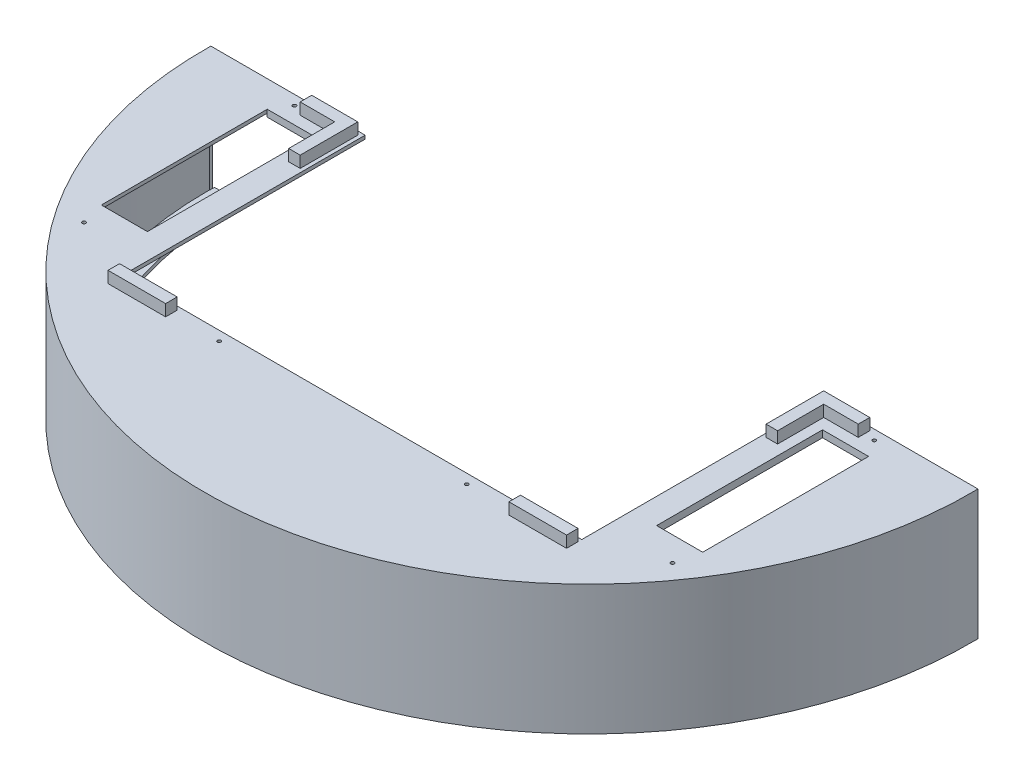
SolidWorks part; units mm, degrees
ref_plane "Front Plane" through (0, 0, 0) normal (0, 0, 1) x (1, 0, 0)
ref_plane "Top Plane" through (0, 0, 0) normal (0, 1, 0) x (1, 0, 0)
ref_plane "Right Plane" through (0, 0, 0) normal (1, 0, 0) x (0, 0, -1)
sketch "Sketch3" plane through (0, 0, 0) normal (0, 1, 0) x (1, 0, 0)
  line L0 (-251.0083, -74.5986) -> (228.9917, -74.5986) construction
  line L1 (228.9917, -74.5986) -> (-11.0083, 165.4014) construction
  line L2 (-11.0083, 165.4014) -> (-251.0083, -74.5986) construction
  line L3 (-11.0083, 165.4014) -> (-11.0083, -74.5986) construction
  line L4 (-230.0083, 0.4014) -> (-230.0083, -149.5986) construction
  line L5 (-230.0083, -149.5986) -> (-272.0083, -149.5986) construction
  line L6 (-272.0083, -149.5986) -> (-272.0083, -169.5986) construction
  line L7 (-161.0083, -209.5986) -> (138.9917, -209.5986) construction
  line L8 (-230.0083, 0.4014) -> (-272.0083, 0.4014) construction
  line L9 (-272.0083, 0.4014) -> (-272.0083, 110.4014) construction
  line L10 (-272.0083, 110.4014) -> (-121.0083, 282.0601) construction
  line L11 (-161.0083, -209.5986) -> (-272.0083, -169.5986) construction
  line L12 (249.9917, 110.4014) -> (98.9917, 282.0601) construction
  line L13 (138.9917, -209.5986) -> (249.9917, -169.5986) construction
  line L14 (249.9917, -149.5986) -> (249.9917, -169.5986) construction
  line L15 (207.9917, -149.5986) -> (249.9917, -149.5986) construction
  line L16 (207.9917, 0.4014) -> (207.9917, -149.5986) construction
  line L17 (207.9917, 0.4014) -> (249.9917, 0.4014) construction
  line L18 (249.9917, 0.4014) -> (249.9917, 110.4014) construction
  arc A0 (98.9917, 282.0601) -> (-121.0083, 282.0601) centre (-11.0083, 187.4993) ccw construction
  circle A1 centre (-11.0083, 15.1744) radius 330
  circle A2 centre (-11.0083, 15.1744) radius 333
  point P22 (-11.0083, 282.0601)
  dimension "D1" = 480
  dimension "D2" = 21
  dimension "D3" = 75
  dimension "D4" = 75
  dimension "D5" = 42
  dimension "D6" = 20
  dimension "D7" = 110
  dimension "D8" = 110
  dimension "D9" = 240
  dimension "D10" = 20
  dimension "D11" = 21
  dimension "D12" = 21
  dimension "D13" = 150
  dimension "D14" = 42
  dimension "D15" = 300
  dimension "D16" = 3
extrude "Boss-Extrude2" add sketch "Sketch3" along normal blind 3 and the other way blind 109.6
ref_plane "Plane2" through (0, -104.6, 0) normal (0, -1, 0) x (-1, 0, 0)
sketch "Sketch5" plane through (0, -104.6, 0) normal (0, -1, 0) x (1, 0, 0)
  line L0 (-166.0669, -282.0601) -> (144.0503, -282.0601) construction
  line L1 (-164.3328, -283.0601) -> (142.3162, -283.0601)
  circle A0 centre (-11.0083, -15.1744) radius 330
  circle A1 centre (-11.0083, -15.1744) radius 308.6602 construction
  arc A2 (-164.3328, -283.0601) -> (142.3162, -283.0601) centre (-11.0083, -15.1744) cw
  dimension "D1" = 1
extrude "Boss-Extrude4" add sketch "Sketch5" against normal blind 3
sketch "Sketch6" plane through (0, 0, 0) normal (0, 1, 0) x (1, 0, 0)
  line L0 (-272.0083, 0.4014) -> (-272.0083, 110.4014) construction
  line L1 (249.9917, 0.4014) -> (249.9917, 110.4014) construction
  line L2 (249.9917, 110.4014) -> (98.9917, 282.0601) construction
  line L3 (-272.0083, 110.4014) -> (-121.0083, 282.0601) construction
  line L4 (-82.3339, 288.1744) -> (60.3173, 288.1744)
  line L5 (-100.8342, 348.1744) -> (51.1218, 348.1744) construction
  line L6 (-247.0083, 20.4014) -> (-247.0083, 100.9705)
  line L7 (-230.0083, 0.4014) -> (-230.0083, -149.5986) construction
  line L8 (-247.0083, 20.4014) -> (-210.0083, 20.4014)
  line L9 (224.9917, 20.4014) -> (224.9917, 100.9705)
  line L10 (207.9917, 0.4014) -> (249.9917, 0.4014) construction
  line L11 (224.9917, 20.4014) -> (187.9917, 20.4014)
  line L12 (-247.0083, 100.9705) -> (-82.3339, 288.1744)
  line L13 (224.9917, 100.9705) -> (60.3173, 288.1744)
  line L14 (-210.0083, 20.4014) -> (-210.0083, -191.941) construction
  line L15 (187.9917, 20.4014) -> (187.9917, -191.941) construction
  line L16 (138.9917, -209.5986) -> (249.9917, -169.5986) construction
  line L17 (-161.0083, -209.5986) -> (-272.0083, -169.5986) construction
  line L18 (-210.0083, -189.5986) -> (187.9917, -189.5986)
  line L19 (-161.0083, -209.5986) -> (138.9917, -209.5986) construction
  line L20 (-210.0083, 20.4014) -> (-210.0083, -189.5986)
  line L21 (187.9917, -189.5986) -> (187.9917, 20.4014)
  line L22 (-230.0083, 0.4014) -> (-272.0083, 0.4014) construction
  circle A0 centre (-11.0083, 15.1744) radius 333
  circle A1 centre (-11.0083, 15.1744) radius 273 construction
  dimension "D1" = 60
  dimension "D2" = 25
  dimension "D3" = 25
  dimension "D4" = 25
  dimension "D5" = 25
  dimension "D6" = 60
  dimension "D7" = 20
  dimension "D8" = 20
  dimension "D9" = 20
  dimension "D10" = 20
extrude "Boss-Extrude6" add sketch "Sketch6" along normal blind 3 contours A0 L21 L18 L20 L8 L6 L12 L4 L13 L9 L11
ref_plane "Plane4" through (0, -5, 0) normal (0, 1, 0) x (1, 0, 0)
sketch "Sketch17" plane through (0, -5, 0) normal (0, 1, 0) x (1, 0, 0)
  line L2 (142.3162, 283.0601) -> (-164.3328, 283.0601)
  line L3 (142.3162, 283.0601) -> (-164.3328, 283.0601)
  arc A2 (-164.3328, 283.0601) -> (142.3162, 283.0601) centre (-11.0083, 15.1744) ccw
  arc A3 (-164.3328, 283.0601) -> (142.3162, 283.0601) centre (-11.0083, 15.1744) ccw
  circle A5 centre (-11.0083, 15.1744) radius 330
  circle A6 centre (-11.0083, 15.1744) radius 330
  dimension "D1" = 0
  dimension "D2" = 0
extrude "Boss-Extrude9" add sketch "Sketch17" against normal blind 3
sketch "Sketch18" plane through (0, -5, 0) normal (0, 1, 0) x (1, 0, 0)
  line L1 (-363.4395, 20.4014) -> (349.2765, 20.4014)
  line L2 (-363.4395, 20.4014) -> (-363.4395, 366.6238)
  line L3 (-363.4395, 366.6238) -> (349.2765, 366.6238)
  line L4 (349.2765, 20.4014) -> (349.2765, 366.6238)
extrude "Cut-Extrude1" cut sketch "Sketch18" against normal through all both and the other way through all
sketch "Sketch19" plane through (0, 3, 0) normal (0, 1, 0) x (1, 0, 0)
  line L1 (-213.2083, 17.2014) -> (-223.2083, 17.2014)
  line L2 (-213.2083, 17.2014) -> (-213.2083, -32.7986)
  line L3 (-213.2083, -32.7986) -> (-223.2083, -32.7986)
  line L4 (-223.2083, 17.2014) -> (-223.2083, -32.7986)
  line L5 (191.1917, 17.2014) -> (201.1917, 17.2014)
  line L6 (191.1917, 17.2014) -> (191.1917, -32.7986)
  line L7 (191.1917, -32.7986) -> (201.1917, -32.7986)
  line L8 (201.1917, 17.2014) -> (201.1917, -32.7986)
  line L9 (-210.0083, -192.7986) -> (-160.0083, -192.7986)
  line L10 (-210.0083, -192.7986) -> (-210.0083, -202.7986)
  line L11 (-210.0083, -202.7986) -> (-160.0083, -202.7986)
  line L12 (-210.0083, 20.4014) -> (-210.0083, -189.5986) construction
  line L13 (201.1917, 17.2014) -> (231.1917, 17.2014)
  line L14 (201.1917, 17.2014) -> (201.1917, 7.2014)
  line L15 (201.1917, 7.2014) -> (231.1917, 7.2014)
  line L16 (231.1917, 17.2014) -> (231.1917, 7.2014)
  line L17 (-223.2083, 17.2014) -> (-253.2083, 17.2014)
  line L18 (-223.2083, 17.2014) -> (-223.2083, 7.2014)
  line L19 (-223.2083, 7.2014) -> (-253.2083, 7.2014)
  line L20 (-253.2083, 17.2014) -> (-253.2083, 7.2014)
  line L21 (-343.9673, 20.4014) -> (-210.0083, 20.4014) construction
  line L22 (321.9507, 20.4014) -> (187.9917, 20.4014) construction
  line L23 (187.9917, -189.5986) -> (187.9917, 20.4014) construction
  line L24 (-210.0083, -189.5986) -> (187.9917, -189.5986) construction
  line L29 (-160.0083, -192.7986) -> (-160.0083, -202.7986)
  line L30 (187.9917, -202.7986) -> (137.9917, -202.7986)
  line L31 (187.9917, -202.7986) -> (187.9917, -192.7986)
  line L32 (187.9917, -192.7986) -> (137.9917, -192.7986)
  line L33 (137.9917, -202.7986) -> (137.9917, -192.7986)
  dimension "D5" = 50
  dimension "D6" = 10
  dimension "D7" = 30
  dimension "D8" = 10
  dimension "D9" = 30
  dimension "D10" = 10
  dimension "D3" = 3.2
  dimension "D4" = 3.2
  dimension "D2" = 3.2
  dimension "D11" = 3.2
  dimension "D15" = 50
  dimension "D16" = 10
  dimension "D17" = 50
extrude "Boss-Extrude10" add sketch "Sketch19" along normal blind 10 contours L29 L9 L10 L11 | L33 L30 L31 L32 | L8 L5 L6 L7 | L16 L13 L8 L15 | L17 L20 L19 L4 | L1 L4 L3 L2
sketch "Sketch20" plane through (0, 0, -20.4014) normal (0, 0, -1) x (-1, 0, 0)
  line L0 (-318.9503, 0) -> (-318.9917, -109.6) construction
  line L1 (-318.9917, -109.6) -> (-320.4505, -109.6) construction
  line L2 (-318.9503, -109.6) -> (-321.9507, -109.6) construction
  line L3 (-320.4505, -109.6) -> (-320.4505, 0) construction
  line L4 (-320.4505, 0) -> (-318.9503, 0) construction
  line L5 (340.9669, 0) -> (340.9669, -109.6) construction
  line L6 (340.9669, -109.6) -> (342.4671, -109.6) construction
  line L7 (343.9673, -109.6) -> (340.9669, -109.6) construction
  line L8 (342.4671, -109.6) -> (342.4671, 0) construction
  line L9 (342.4671, 0) -> (340.9669, 0) construction
  line L10 (-318.9917, -109.6) -> (341.0083, -109.6) construction
  line L11 (-320.6505, 0) -> (-318.7917, 0)
  line L12 (-320.6505, 0) -> (-320.6505, -109.6)
  line L13 (-320.6505, -109.6) -> (-318.7917, -109.6)
  line L14 (-318.7917, 0) -> (-318.7917, -109.6)
  line L15 (-318.9917, 0) -> (341.0083, 0) construction
  line L16 (342.6671, -109.6) -> (340.7669, -109.6)
  line L17 (342.6671, -109.6) -> (342.6671, 0)
  line L18 (342.6671, 0) -> (340.7669, 0)
  line L19 (340.7669, -109.6) -> (340.7669, 0)
  dimension "D1" = 0.2
  dimension "D2" = 0.2
  dimension "D3" = 0.2
  dimension "D4" = 0.2
extrude "Cut-Extrude2" cut sketch "Sketch20" against normal blind 4.1
sketch "Sketch23" plane through (0, 3, 0) normal (0, 1, 0) x (1, 0, 0)
  circle A0 centre (-266.4306, -167.218) radius 1.5
  circle A1 centre (-262.8359, 11.8788) radius 1.5
  circle A2 centre (240.3837, 11.8788) radius 1.5
  circle A3 centre (244.9311, -167.7801) radius 1.5
  circle A4 centre (-118.5083, -197.8799) radius 1.5
  circle A5 centre (96.4917, -197.8799) radius 1.5
extrude "Cut-Extrude3" cut sketch "Sketch23" against normal up to surface (11 mm away)
sketch "Sketch24" plane through (0, 3, 0) normal (0, 1, 0) x (1, 0, 0)
  line L0 (-230.0083, 0.4014) -> (-230.0083, -149.5986) construction
  line L1 (-272.0083, -2.5986) -> (-232.0083, -2.5986)
  line L2 (-272.0083, -2.5986) -> (-272.0083, -146.5986)
  line L3 (-272.0083, -146.5986) -> (-232.0083, -146.5986)
  line L4 (-232.0083, -2.5986) -> (-232.0083, -146.5986)
  line L5 (-230.0083, -149.5986) -> (-272.0083, -149.5986) construction
  line L6 (-230.0083, 0.4014) -> (-272.0083, 0.4014) construction
  line L7 (-272.0083, 0.4014) -> (-272.0083, 110.4014) construction
  line L8 (207.9917, 0.4014) -> (249.9917, 0.4014) construction
  line L9 (209.9917, -2.5986) -> (249.9917, -2.5986)
  line L10 (209.9917, -2.5986) -> (209.9917, -146.5986)
  line L11 (209.9917, -146.5986) -> (249.9917, -146.5986)
  line L12 (249.9917, -2.5986) -> (249.9917, -146.5986)
  line L13 (207.9917, -149.5986) -> (249.9917, -149.5986) construction
  line L14 (207.9917, 0.4014) -> (207.9917, -149.5986) construction
  line L15 (249.9917, -149.5986) -> (249.9917, -169.5986) construction
  dimension "D1" = 2
  dimension "D2" = 3
  dimension "D3" = 3
  dimension "D4" = 3
  dimension "D5" = 3
  dimension "D6" = 2
extrude "Cut-Extrude4" cut sketch "Sketch24" against normal up to surface (3 mm away)
sketch "Sketch25" plane through (0, 0, 0) normal (0, -1, 0) x (1, 0, 0)
  line L0 (-272.0083, 149.5986) -> (-272.0083, 146.5986)
  line L1 (-272.0083, 146.5986) -> (-232.0083, 146.5986)
  line L2 (-232.0083, 146.5986) -> (-232.0083, 2.5986)
  line L3 (-232.0083, 2.5986) -> (-272.0083, 2.5986)
  line L4 (-272.0083, 2.5986) -> (-272.0083, -0.4014)
  line L5 (-230.0083, -0.4014) -> (-272.0083, -0.4014) construction
  line L6 (-272.0083, -0.4014) -> (-272.0083, -110.4014) construction
  line L7 (-272.0083, -0.4014) -> (-230.0083, -0.4014)
  line L8 (-230.0083, -0.4014) -> (-230.0083, 149.5986)
  line L9 (-230.0083, 149.5986) -> (-272.0083, 149.5986)
  line L10 (249.9917, 149.5986) -> (207.9917, 149.5986)
  line L11 (207.9917, 149.5986) -> (207.9917, -0.4014)
  line L12 (207.9917, -0.4014) -> (249.9917, -0.4014)
  line L13 (249.9917, -0.4014) -> (249.9917, 2.5986)
  line L14 (249.9917, 2.5986) -> (209.9917, 2.5986)
  line L15 (209.9917, 2.5986) -> (209.9917, 146.5986)
  line L16 (209.9917, 146.5986) -> (249.9917, 146.5986)
  line L17 (249.9917, 146.5986) -> (249.9917, 149.5986)
extrude "Boss-Extrude11" add sketch "Sketch25" along normal blind 3
equation "\"camera-height\"= 100mm"
equation "\"case-thickness\"= 3mm"
equation "\"D16@Sketch3\"=\"case-thickness\""
equation "\"D1@Boss-Extrude2\"=\"case-thickness\""
equation "\"D3@Sketch19\"=\"case-thickness\"+0.2mm"
